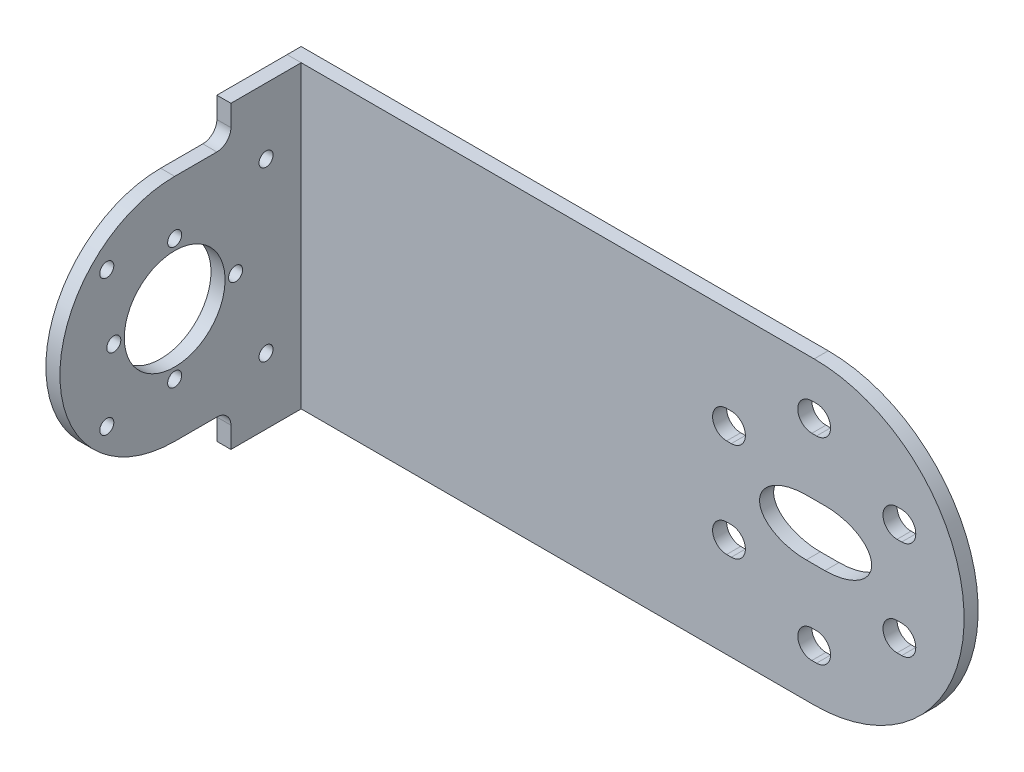
SolidWorks part; units mm, degrees
material "1060 Alloy"
ref_plane "Front Plane" through (0, 0, 0) normal (0, 0, 1) x (1, 0, 0)
ref_plane "Top Plane" through (0, 0, 0) normal (0, 1, 0) x (1, 0, 0)
ref_plane "Right Plane" through (0, 0, 0) normal (1, 0, 0) x (0, 0, -1)
sketch "Sketch1" plane through (0, 0, 0) normal (0, 0, 1) x (1, 0, 0)
  line L0 (-112.5, 32) -> (0, 32)
  line L1 (-112.5, -32) -> (0, -32)
  line L2 (17.6865, 10.5) -> (18.6865, 10.5) construction
  line L3 (-112.5, 32) -> (-112.5, -32)
  line L4 (-113, -33) -> (-113, 33) construction
  line L7 (17.6865, 13.5) -> (18.6865, 13.5)
  line L8 (17.6865, 7.5) -> (18.6865, 7.5)
  line L9 (17.6865, -10.5) -> (18.6865, -10.5) construction
  line L10 (17.6865, -7.5) -> (18.6865, -7.5)
  line L11 (17.6865, -13.5) -> (18.6865, -13.5)
  line L12 (-0.5, -21) -> (0.5, -21) construction
  line L13 (-0.5, -18) -> (0.5, -18)
  line L14 (-0.5, -24) -> (0.5, -24)
  line L15 (-18.6865, -10.5) -> (-17.6865, -10.5) construction
  line L16 (-18.6865, -7.5) -> (-17.6865, -7.5)
  line L17 (-18.6865, -13.5) -> (-17.6865, -13.5)
  line L18 (-17.6865, 10.5) -> (-18.6865, 10.5) construction
  line L19 (-17.6865, 7.5) -> (-18.6865, 7.5)
  line L20 (-17.6865, 13.5) -> (-18.6865, 13.5)
  line L21 (0.5, 21) -> (-0.5, 21) construction
  line L22 (0.5, 18) -> (-0.5, 18)
  line L23 (0.5, 24) -> (-0.5, 24)
  arc A1 (17.6865, 13.5) -> (17.6865, 7.5) centre (17.6865, 10.5) ccw
  circle A2 centre (18.1865, -10.5) radius 3 construction
  circle A3 centre (0, -21) radius 3 construction
  circle A4 centre (-18.1865, -10.5) radius 3 construction
  circle A5 centre (-18.1865, 10.5) radius 3 construction
  circle A6 centre (0, 21) radius 3 construction
  arc A7 (0, -32) -> (0, 32) centre (0, 0) ccw
  arc A11 (18.6865, 7.5) -> (18.6865, 13.5) centre (18.6865, 10.5) ccw
  circle A12 centre (18.1865, 10.5) radius 3 construction
  arc A13 (17.6865, -7.5) -> (17.6865, -13.5) centre (17.6865, -10.5) ccw
  arc A14 (18.6865, -13.5) -> (18.6865, -7.5) centre (18.6865, -10.5) ccw
  arc A15 (-0.5, -18) -> (-0.5, -24) centre (-0.5, -21) ccw
  arc A16 (0.5, -24) -> (0.5, -18) centre (0.5, -21) ccw
  arc A17 (-18.6865, -7.5) -> (-18.6865, -13.5) centre (-18.6865, -10.5) ccw
  arc A18 (-17.6865, -13.5) -> (-17.6865, -7.5) centre (-17.6865, -10.5) ccw
  arc A19 (-17.6865, 7.5) -> (-17.6865, 13.5) centre (-17.6865, 10.5) ccw
  arc A20 (-18.6865, 13.5) -> (-18.6865, 7.5) centre (-18.6865, 10.5) ccw
  arc A21 (0.5, 18) -> (0.5, 24) centre (0.5, 21) ccw
  arc A22 (-0.5, 24) -> (-0.5, 18) centre (-0.5, 21) ccw
  circle A23 centre (18.1865, -10.5) radius 3 construction
  circle A24 centre (0, -21) radius 3 construction
  circle A25 centre (-18.1865, -10.5) radius 3 construction
  circle A26 centre (-18.1865, 10.5) radius 3 construction
  circle A27 centre (0, 21) radius 3 construction
  arc A28 (0, -33) -> (0, 33) centre (0, 0) ccw construction
  point P3 (18.1865, 10.5)
  point P18 (0, 0)
  point P33 (18.1865, -10.5)
  point P41 (0, -21)
  point P48 (-18.1865, -10.5)
  point P56 (-18.1865, 10.5)
  point P62 (0, 21)
  dimension "D2" = 1
  dimension "D3" = 0.5
  dimension "D1" = 1
extrude "Boss-Extrude1" add sketch "Sketch1" along normal blind 3 contours A7 L0 L3 L1
sketch "Sketch2" plane through (-112.5, 0, 0) normal (-1, 0, 0) x (0, 0, 1)
  line L0 (3, -32) -> (18, -32)
  line L1 (18, -32) -> (18, -27.5)
  line L2 (21, -24.5) -> (30, -24.5)
  line L3 (0, 0) -> (46.5, 0) construction
  line L4 (3, 32) -> (18, 32)
  line L5 (18, 32) -> (18, 27.5)
  line L6 (21, 24.5) -> (30, 24.5)
  line L7 (44.4957, 14.4957) -> (30, 0) construction
  line L8 (54.5, 0) -> (46.5, 0) construction
  line L9 (17.8585, -11.1729) -> (3.1415, -24.7158) construction
  line L10 (17.8585, -11.1729) -> (30, 0) construction
  circle A0 centre (30, 0) radius 36.5 construction
  circle A2 centre (10.5, -17.9444) radius 1.5
  circle A3 centre (30, 13) radius 1.5
  circle A4 centre (30, 13) radius 1.5 construction
  circle A5 centre (43, 0) radius 1.5
  circle A6 centre (30, -13) radius 1.5
  circle A7 centre (17, 0) radius 1.5
  circle A10 centre (30, 0) radius 10.75
  arc A11 (18, -27.5) -> (21, -24.5) centre (21, -27.5) cw
  arc A12 (18, 27.5) -> (21, 24.5) centre (21, 27.5) ccw
  circle A13 centre (10.5, 17.9444) radius 1.5
  arc A15 (27, -24.3156) -> (27, 24.3156) centre (30, 0) ccw construction
  arc A17 (30, -24.5) -> (30, 24.5) centre (30, 0) ccw
  circle A18 centre (30, 0) radius 10.5 construction
  circle A19 centre (30, 0) radius 16.5 construction
  circle A20 centre (30, 0) radius 20.5 construction
  circle A21 centre (30, 0) radius 36.5 construction
  circle A22 centre (44.4957, 14.4957) radius 1.5
  circle A23 centre (44.4957, -14.4957) radius 1.5
  point P23 (50.5, 0)
  point P34 (30, 0)
  point P58 (10.5, -17.9444)
  point P62 (10.5, -32)
  dimension "D1" = 4
  dimension "D4" = 0.25
  dimension "D5" = 3
  dimension "D7" = 3
  dimension "D2" = 15
  dimension "D6" = 45
  dimension "D3" = 4
extrude "Boss-Extrude2" add sketch "Sketch2" against normal blind 3 separate body
ref_plane "Plane1" through (-68.3993, 0, -51.5425) normal (0.7986, 0, 0.6018) x (0, 1, 0)
sketch "Sketch3" plane through (-68.3993, 0, -51.5425) normal (0.7986, 0, 0.6018) x (0, 1, 0)
  circle A0 centre (0, 1.0136) radius 6
  circle A1 centre (0, 1.0136) radius 6 construction
extrude "Cut-Extrude1" cut sketch "Sketch3" along normal through all
sketch "Sketch4" plane through (0, 0, 3) normal (0, 0, 1) x (1, 0, 0)
  line L0 (2.2968, -6) -> (-1.6843, -6)
  line L2 (-1.6843, 6) -> (2.2968, 6)
  ellipse E0 centre (-1.6843, 0) end of major axis (-11.6542, 0) minor radius 6 (-1.6843, 6) -> (-1.6843, -6) ccw
  ellipse E1 centre (-1.6843, 0) end of major axis (-11.6542, 0) minor radius 6 construction
  ellipse E3 centre (2.2968, 0) end of major axis (12.2667, 0) minor radius 6 (2.2968, -6) -> (2.2968, 6) ccw
  ellipse E4 centre (2.2968, 0) end of major axis (-7.673, 0) minor radius 6 construction
extrude "Cut-Extrude2" cut sketch "Sketch4" against normal through all
